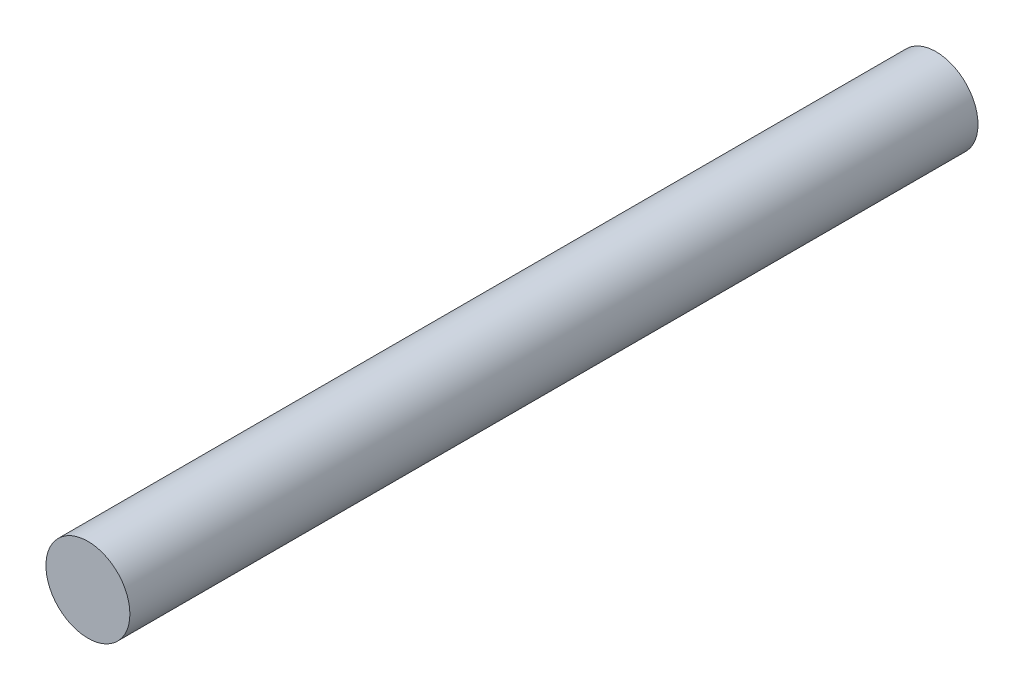
SolidWorks part; units mm, degrees
ref_plane "Front Plane" through (0, 0, 0) normal (1, 0, 0) x (0, 1, 0)
ref_plane "Top Plane" through (0, 0, 0) normal (0, 0, 1) x (0, 1, 0)
ref_plane "Right Plane" through (0, 0, 0) normal (0, 1, 0) x (-1, 0, 0)
sketch "Sketch1" plane through (0, 0, 0) normal (0, 0, 1) x (0, 1, 0)
  circle A0 centre (0, 0) radius 5
  dimension "D1" = 10
extrude "Boss-Extrude1" add sketch "Sketch1" along normal blind 101
